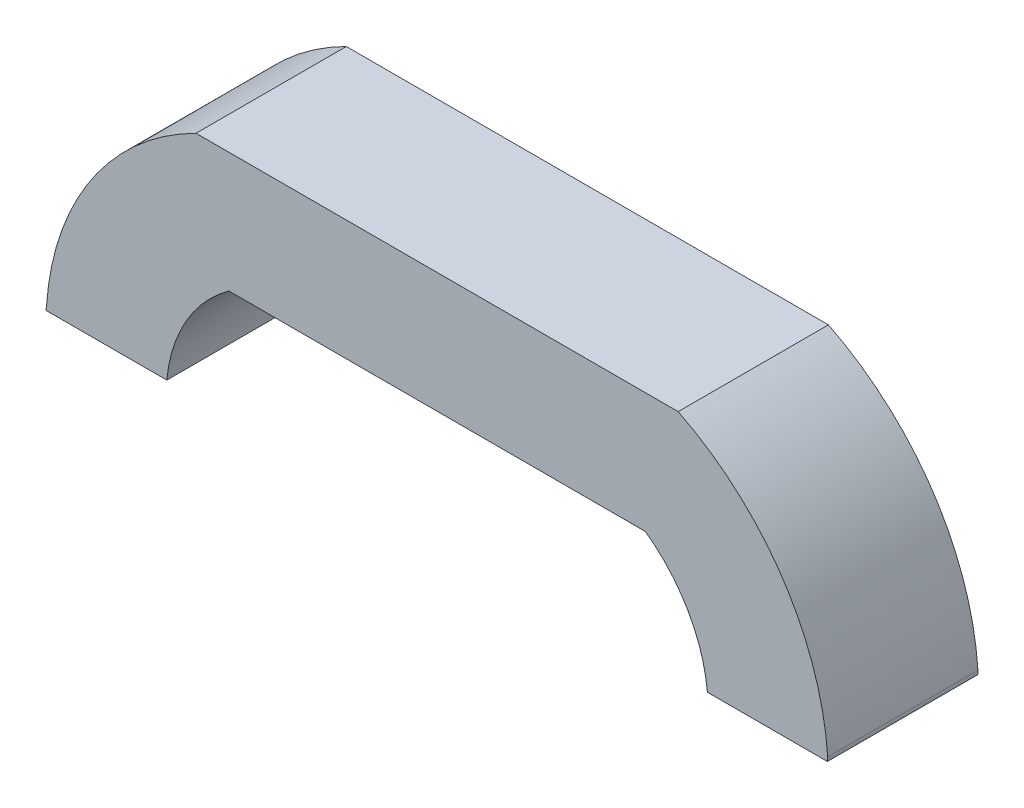
SolidWorks part; units mm, degrees
ref_plane "Front Plane" through (0, 0, 0) normal (0, 0, 1) x (1, 0, 0)
ref_plane "Top Plane" through (0, 0, 0) normal (0, 1, 0) x (1, 0, 0)
ref_plane "Right Plane" through (0, 0, 0) normal (1, 0, 0) x (0, 0, -1)
sketch "Sketch2" plane through (0, 0, 0) normal (0, 0, 1) x (1, 0, 0)
  line L0 (-37.5918, 28) -> (33.5641, 28) construction
  line L1 (55, 0) -> (-55, 0) construction
  line L2 (0, -55) -> (0, 55) construction
  line L3 (33.5641, 28) -> (37.5918, 28)
  line L4 (33.5641, 18) -> (34.6541, 18)
  line L5 (-34.6541, 18) -> (33.5641, 18)
  line L6 (-55, 0) -> (55, 0) construction
  line L7 (33.5641, 38) -> (40.1058, 38)
  line L8 (-40.1058, 38) -> (33.5641, 38)
  line L9 (-65.0636, 0) -> (-44.9677, 0)
  line L10 (44.9677, 0) -> (64.9299, 0)
  arc A0 (-37.5918, 28) -> (-55, 0) centre (-19.948, -2.3811) ccw construction
  arc A1 (37.5918, 28) -> (55, 0) centre (19.948, -2.3811) cw construction
  arc A2 (34.6541, 18) -> (44.9677, 0) centre (19.948, -2.3811) cw
  arc A3 (-34.6541, 18) -> (-44.9677, 0) centre (-19.948, -2.3811) ccw
  arc A4 (40.1058, 38) -> (64.977, 0.6777) centre (19.948, -2.3811) cw
  arc A5 (-34.6541, 18) -> (-45.023, -0.6777) centre (-19.948, -2.3811) ccw construction
  arc A6 (34.6541, 18) -> (45.023, -0.6777) centre (19.948, -2.3811) cw construction
  arc A7 (-40.1058, 38) -> (-64.977, 0.6777) centre (-19.948, -2.3811) ccw
  arc A8 (-64.977, 0.6777) -> (-65.0636, 0) centre (-49.6941, -1.6199) ccw
  arc A9 (64.977, 0.6777) -> (64.9299, 0) centre (63.0299, 0.4725) cw
  dimension "D1" = 28
  dimension "D2" = 55
  dimension "D3" = 10
  dimension "D4" = 10
extrude "Boss-Extrude1" add sketch "Sketch2" along normal blind 25
sketch "Sketch3" plane through (0, 0, 0) normal (0, -1, 0) x (1, 0, 0)
  line L0 (0, -13.75) -> (0, 13.75) construction
  line L1 (0, 25) -> (0, 30.4597) construction
  line L2 (-34.6541, 25) -> (34.6541, 25) construction
  line L3 (0, -1.2974) -> (0, 47.2632) construction
  circle A0 centre (-55, 12.5) radius 2
  circle A1 centre (55, 12.5) radius 2
  dimension "D2" = 4
  dimension "D1" = 55
extrude "Cut-Extrude1" cut sketch "Sketch3" against normal blind 10
